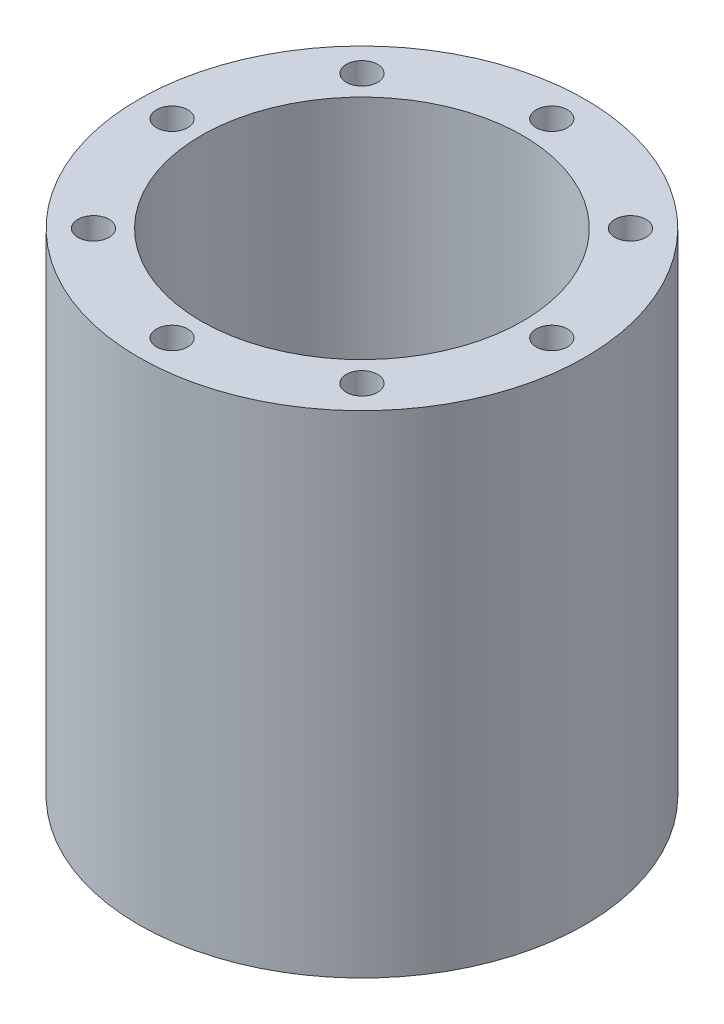
SolidWorks part; units mm, degrees
material "Ст 3 ГОСТ 380-88"
ref_plane "Front Plane" through (0, 0, 0) normal (0, 0, 1) x (1, 0, 0)
ref_plane "Top Plane" through (0, 0, 0) normal (0, 1, 0) x (1, 0, 0)
ref_plane "Right Plane" through (0, 0, 0) normal (1, 0, 0) x (0, 0, -1)
sketch "Sketch1" plane through (0, 0, 0) normal (0, 1, 0) x (1, 0, 0)
  line L0 (0, 151.3926) -> (0, 40) construction
  line L1 (-152.186, 0) -> (-40, 0) construction
  line L5 (22.5897, 10.71) -> (20.28, 9.7533) construction
  line L6 (20.7584, 8.5984) -> (21.2368, 7.4436) construction
  line L7 (21.2368, 7.4436) -> (23.5465, 8.4003) construction
  line L8 (0, 0) -> (20.7584, 8.5984) construction
  line L9 (23.5465, -8.4003) -> (21.2368, -7.4436) construction
  line L10 (21.2368, -7.4436) -> (20.28, -9.7533) construction
  line L11 (20.28, -9.7533) -> (22.5897, -10.71) construction
  line L12 (10.71, -22.5897) -> (9.7533, -20.28) construction
  line L13 (9.7533, -20.28) -> (8.5984, -20.7584) construction
  line L14 (7.4436, -21.2368) -> (8.4003, -23.5465) construction
  line L15 (-8.4003, -23.5465) -> (-7.4436, -21.2368) construction
  line L16 (-7.4436, -21.2368) -> (-8.5984, -20.7584) construction
  line L17 (-9.7533, -20.28) -> (-10.71, -22.5897) construction
  line L18 (-22.5897, -10.71) -> (-20.28, -9.7533) construction
  line L19 (-20.28, -9.7533) -> (-21.2368, -7.4436) construction
  line L20 (-21.2368, -7.4436) -> (-23.5465, -8.4003) construction
  line L21 (-23.5465, 8.4003) -> (-21.2368, 7.4436) construction
  line L22 (-21.2368, 7.4436) -> (-20.28, 9.7533) construction
  line L23 (-20.28, 9.7533) -> (-22.5897, 10.71) construction
  line L24 (-10.71, 22.5897) -> (-9.7533, 20.28) construction
  line L25 (-9.7533, 20.28) -> (-7.4436, 21.2368) construction
  line L26 (-7.4436, 21.2368) -> (-8.4003, 23.5465) construction
  line L27 (8.4003, 23.5465) -> (7.4436, 21.2368) construction
  line L28 (7.4436, 21.2368) -> (9.7533, 20.28) construction
  line L29 (9.7533, 20.28) -> (10.71, 22.5897) construction
  line L30 (0, 0) -> (8.5984, -20.7584) construction
  line L31 (-8.5984, -20.7584) -> (0, 0) construction
  line L32 (-4, 24.6779) -> (-4, 40) construction
  line L33 (0, 40) -> (4, 40) construction
  line L34 (4, 40) -> (4, 24.6779) construction
  line L35 (14.6215, 20.2784) -> (25.4558, 31.1127) construction
  line L36 (25.4558, 31.1127) -> (31.1127, 25.4558) construction
  line L37 (31.1127, 25.4558) -> (20.2784, 14.6215) construction
  line L38 (24.6779, 4) -> (40, 4) construction
  line L39 (40, 0) -> (40, -4) construction
  line L40 (40, -4) -> (24.6779, -4) construction
  line L41 (20.2784, -14.6215) -> (31.1127, -25.4558) construction
  line L42 (31.1127, -25.4558) -> (25.4558, -31.1127) construction
  line L43 (25.4558, -31.1127) -> (14.6215, -20.2784) construction
  line L44 (4, -24.6779) -> (4, -40) construction
  line L45 (0, -40) -> (-4, -40) construction
  line L46 (-4, -40) -> (-4, -24.6779) construction
  line L47 (-14.6215, -20.2784) -> (-25.4558, -31.1127) construction
  line L48 (-25.4558, -31.1127) -> (-31.1127, -25.4558) construction
  line L49 (-31.1127, -25.4558) -> (-20.2784, -14.6215) construction
  line L50 (-24.6779, -4) -> (-40, -4) construction
  line L51 (-40, 0) -> (-40, 4) construction
  line L52 (-40, 4) -> (-24.6779, 4) construction
  line L53 (-20.2784, 14.6215) -> (-31.1127, 25.4558) construction
  line L54 (-31.1127, 25.4558) -> (-25.4558, 31.1127) construction
  line L55 (-25.4558, 31.1127) -> (-14.6215, 20.2784) construction
  line L56 (-40, 0) -> (-25, 0) construction
  line L57 (-25, 0) -> (25, 0) construction
  line L58 (0, 40) -> (0, 25) construction
  line L59 (0, 25) -> (0, -25) construction
  line L60 (23.097, 9.5671) -> (87.9274, 36.4207) construction
  line L61 (25, 0) -> (40, 0) construction
  line L62 (40, 0) -> (146.8463, 0) construction
  line L63 (0, -25) -> (0, -40) construction
  line L64 (0, -40) -> (0, -120.313) construction
  line L65 (-4, 40) -> (0, 40) construction
  line L66 (40, 4) -> (40, 0) construction
  line L67 (4, -40) -> (0, -40) construction
  line L68 (-40, -4) -> (-40, 0) construction
  line L69 (20.7584, 8.5984) -> (23.097, 9.5671) construction
  line L70 (8.5984, -20.7584) -> (7.4436, -21.2368) construction
  line L71 (-8.5984, -20.7584) -> (-9.7533, -20.28) construction
  line L72 (20.28, 9.7533) -> (20.7584, 8.5984) construction
  circle A0 centre (0, 0) radius 500 construction
  circle A1 centre (0, 0) radius 497 construction
  arc A2 (-4, 24.6779) -> (-8.4003, 23.5465) centre (0, 0) ccw construction
  circle A3 centre (0, 0) radius 18
  arc A4 (4, 24.6779) -> (0, 25) centre (0, 0) ccw construction
  arc A5 (0, 25) -> (-4, 24.6779) centre (0, 0) ccw construction
  arc A6 (-22.5897, 10.71) -> (-23.5465, 8.4003) centre (0, 0) ccw construction
  arc A7 (-23.5465, 8.4003) -> (-24.6779, 4) centre (0, 0) ccw construction
  arc A8 (-8.4003, 23.5465) -> (-10.71, 22.5897) centre (0, 0) ccw construction
  arc A9 (-10.71, 22.5897) -> (-14.6215, 20.2784) centre (0, 0) ccw construction
  arc A10 (10.71, 22.5897) -> (8.4003, 23.5465) centre (0, 0) ccw construction
  arc A11 (8.4003, 23.5465) -> (4, 24.6779) centre (0, 0) ccw construction
  arc A12 (23.097, 9.5671) -> (22.5897, 10.71) centre (0, 0) ccw construction
  arc A13 (22.5897, 10.71) -> (20.2784, 14.6215) centre (0, 0) ccw construction
  arc A14 (23.5465, 8.4003) -> (23.097, 9.5671) centre (0, 0) ccw construction
  arc A15 (22.5897, -10.71) -> (23.5465, -8.4003) centre (0, 0) ccw construction
  arc A16 (23.5465, -8.4003) -> (24.6779, -4) centre (0, 0) ccw construction
  arc A17 (8.4003, -23.5465) -> (10.71, -22.5897) centre (0, 0) ccw construction
  arc A18 (10.71, -22.5897) -> (14.6215, -20.2784) centre (0, 0) ccw construction
  arc A19 (-10.71, -22.5897) -> (-8.4003, -23.5465) centre (0, 0) ccw construction
  arc A20 (-8.4003, -23.5465) -> (-4, -24.6779) centre (0, 0) ccw construction
  arc A21 (-23.5465, -8.4003) -> (-22.5897, -10.71) centre (0, 0) ccw construction
  arc A22 (-22.5897, -10.71) -> (-20.2784, -14.6215) centre (0, 0) ccw construction
  arc A23 (-14.6215, 20.2784) -> (-20.2784, 14.6215) centre (0, 0) ccw construction
  arc A24 (-20.2784, 14.6215) -> (-22.5897, 10.71) centre (0, 0) ccw construction
  arc A25 (20.2784, 14.6215) -> (14.6215, 20.2784) centre (0, 0) ccw construction
  arc A26 (14.6215, 20.2784) -> (10.71, 22.5897) centre (0, 0) ccw construction
  arc A27 (24.6779, -4) -> (25, 0) centre (0, 0) ccw construction
  arc A28 (24.6779, 4) -> (23.5465, 8.4003) centre (0, 0) ccw construction
  arc A29 (25, 0) -> (24.6779, 4) centre (0, 0) ccw construction
  arc A30 (14.6215, -20.2784) -> (20.2784, -14.6215) centre (0, 0) ccw construction
  arc A31 (20.2784, -14.6215) -> (22.5897, -10.71) centre (0, 0) ccw construction
  arc A32 (-4, -24.6779) -> (0, -25) centre (0, 0) ccw construction
  arc A33 (4, -24.6779) -> (8.4003, -23.5465) centre (0, 0) ccw construction
  arc A34 (0, -25) -> (4, -24.6779) centre (0, 0) ccw construction
  arc A35 (-20.2784, -14.6215) -> (-14.6215, -20.2784) centre (0, 0) ccw construction
  arc A36 (-14.6215, -20.2784) -> (-10.71, -22.5897) centre (0, 0) ccw construction
  arc A37 (-24.8936, 2.3046) -> (-25, 0) centre (0, 0) ccw construction
  arc A38 (-24.6779, -4) -> (-23.5465, -8.4003) centre (0, 0) ccw construction
  arc A39 (-25, 0) -> (-24.6779, -4) centre (0, 0) ccw construction
  arc A40 (-16.2115, -13.7387) -> (16.2115, -13.7387) centre (0, 0) ccw construction
  circle A41 centre (0, 21.25) radius 1.75
  circle A42 centre (15.026, 15.026) radius 1.75
  circle A43 centre (21.25, 0) radius 1.75
  circle A44 centre (15.026, -15.026) radius 1.75
  circle A45 centre (0, -21.25) radius 1.75
  circle A46 centre (-15.026, -15.026) radius 1.75
  circle A47 centre (-21.25, 0) radius 1.75
  circle A48 centre (-15.026, 15.026) radius 1.75
  arc A49 (-21.1779, -1.7485) -> (-16.2115, -13.7387) centre (0, 0) ccw construction
  arc A50 (-16.2115, 13.7387) -> (-21.1779, 1.7485) centre (0, 0) ccw construction
  arc A51 (-21.1779, 1.7485) -> (-21.1779, -1.7485) centre (0, 0) ccw construction
  arc A52 (-1.7485, 21.1779) -> (-13.7387, 16.2115) centre (0, 0) ccw construction
  arc A53 (-13.7387, 16.2115) -> (-16.2115, 13.7387) centre (0, 0) ccw construction
  arc A54 (13.7387, 16.2115) -> (1.7485, 21.1779) centre (0, 0) ccw construction
  arc A55 (1.7485, 21.1779) -> (-1.7485, 21.1779) centre (0, 0) ccw construction
  arc A56 (19.6324, 8.132) -> (16.2115, 13.7387) centre (0, 0) ccw construction
  arc A57 (16.2115, 13.7387) -> (13.7387, 16.2115) centre (0, 0) ccw construction
  arc A58 (21.1779, 1.7485) -> (19.6324, 8.132) centre (0, 0) ccw construction
  arc A59 (16.2115, -13.7387) -> (21.1779, -1.7485) centre (0, 0) ccw construction
  arc A60 (21.1779, -1.7485) -> (21.1779, 1.7485) centre (0, 0) ccw construction
  circle A61 centre (0, 0) radius 25
  point P14 (0, 55)
  point P41 (0, 0)
  point P61 (0, 0)
  point P83 (0, 0)
  point P105 (0, 0)
  dimension "D1" = 1000
  dimension "D2" = 994
  dimension "D3" = 50
  dimension "D4" = 36
  dimension "D12" = 42.5
  dimension "D13" = 3.5
  dimension "D5" = 22.5
  dimension "D6" = 1.25
  dimension "D7" = 2.5
  dimension "D9" = 40
  dimension "D10" = 8
  dimension "D8" = 8
  dimension "D11" = 8
  dimension "D14" = 8
extrude "Boss-Extrude1" add sketch "Sketch1" along normal mid plane 55 contours A0 A1 | A2 A3
